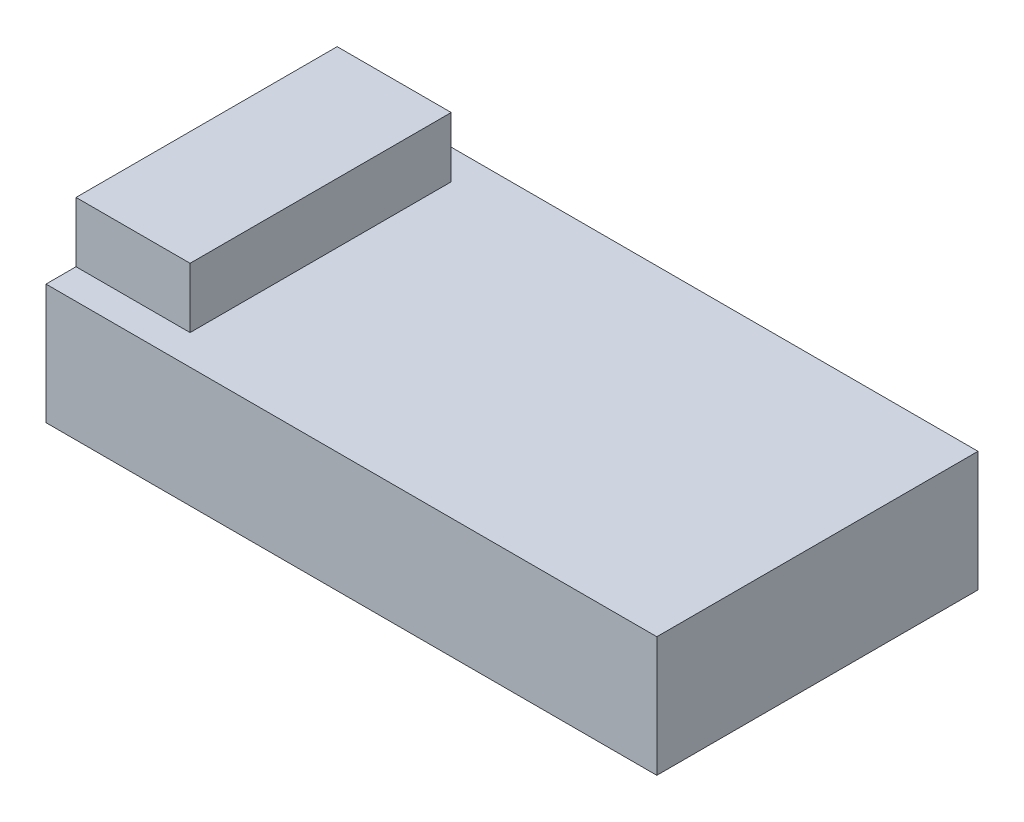
SolidWorks part; units mm, degrees
ref_plane "Front Plane" through (0, 0, 0) normal (0, 0, 1) x (1, 0, 0)
ref_plane "Top Plane" through (0, 0, 0) normal (0, 1, 0) x (1, 0, 0)
ref_plane "Right Plane" through (0, 0, 0) normal (1, 0, 0) x (0, 0, -1)
sketch "Sketch1" plane through (0, 0, 0) normal (0, 1, 0) x (1, 0, 0)
  line L1 (-20.35, -10.7) -> (20.35, -10.7)
  line L2 (-20.35, -10.7) -> (-20.35, 10.7)
  line L3 (-20.35, 10.7) -> (20.35, 10.7)
  line L4 (20.35, -10.7) -> (20.35, 10.7)
  line L5 (0, 10.7) -> (0, -10.7) construction
  line L6 (-20.35, 0) -> (20.35, 0) construction
  point P0 (0, 0)
  dimension "D1" = 21.4
  dimension "D2" = 40.7
extrude "Boss-Extrude1" add sketch "Sketch1" along normal blind 8
sketch "Sketch2" plane through (0, 8, 0) normal (0, 1, 0) x (1, 0, 0)
  line L0 (0, 0) -> (-20.35, 0) construction
  line L1 (-20.35, 10.7) -> (-20.35, -10.7) construction
  line L3 (-20.35, -8.7) -> (-12.75, -8.7)
  line L4 (-20.35, -8.7) -> (-20.35, 8.7)
  line L5 (-20.35, 8.7) -> (-12.75, 8.7)
  line L6 (-12.75, -8.7) -> (-12.75, 8.7)
  line L7 (-16.55, 8.7) -> (-16.55, -8.7) construction
  line L8 (-20.35, 0) -> (-12.75, 0) construction
  point P5 (-16.55, 0)
  dimension "D1" = 17.4
  dimension "D2" = 7.6
extrude "Boss-Extrude2" add sketch "Sketch2" along normal blind 4
